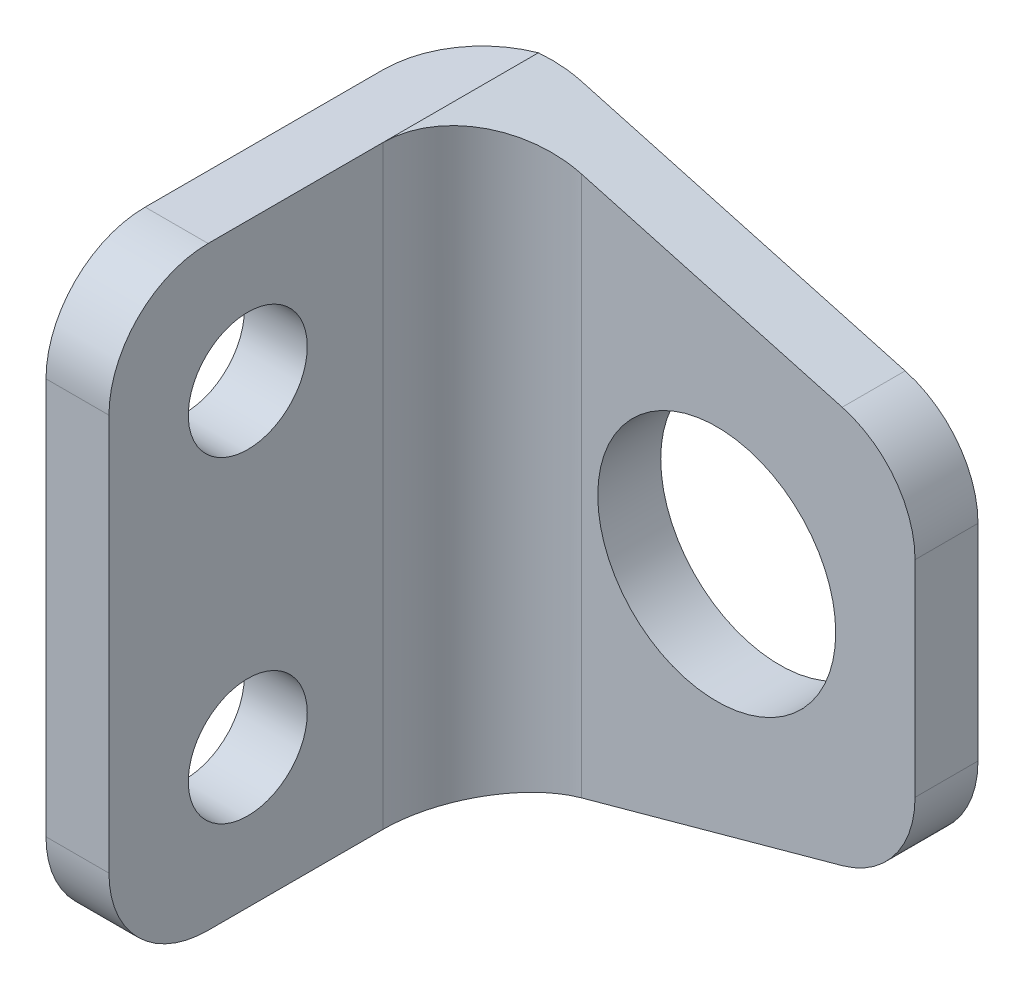
SolidWorks part; units mm, degrees
ref_plane "Front Plane" through (0, 0, 0) normal (0, 0, 1) x (1, 0, 0)
ref_plane "Top Plane" through (0, 0, 0) normal (0, 1, 0) x (1, 0, 0)
ref_plane "Right Plane" through (0, 0, 0) normal (1, 0, 0) x (0, 0, -1)
sketch "Sketch1" plane through (0, 0, 0) normal (1, 0, 0) x (0, 0, -1)
  line L1 (0, 0) -> (22, 0)
  line L2 (0, 0) -> (0, 30)
  line L3 (0, 30) -> (22, 30)
  line L4 (22, 0) -> (22, 30)
  dimension "D1" = 22
  dimension "D2" = 30
extrude "Boss-Extrude1" add sketch "Sketch1" along normal blind 3.175
sketch "Sketch2" plane through (0, 0, -22) normal (0, 0, -1) x (-1, 0, 0)
  line L5 (0, 0) -> (-25, 0)
  line L6 (0, 0) -> (0, 30)
  line L7 (0, 30) -> (-25, 30)
  line L8 (-25, 0) -> (-25, 30)
  dimension "D1" = 25
extrude "Boss-Extrude2" add sketch "Sketch2" against normal blind 3.175
sketch "Sketch3" plane through (0, 0, -22) normal (0, 0, -1) x (-1, 0, 0)
  line L0 (-25, 30) -> (-25, 0) construction
  circle A0 centre (-15, 15) radius 6
  point P4 (-25, 15)
  dimension "D2" = 12
  dimension "D1" = 10
extrude "Cut-Extrude1" cut sketch "Sketch3" against normal through all
sketch "Sketch5" plane through (0, 0, -22) normal (0, 0, -1) x (-1, 0, 0)
  line L4 (-3.175, 30) -> (-25, 24)
  line L9 (-25, 30) -> (-25, 0) construction
  line L10 (-25, 24) -> (-25, 30)
  line L11 (-25, 30) -> (-3.175, 30)
  line L12 (-25, 15) -> (0, 15) construction
  line L13 (-25, 30) -> (-25, 0) construction
  line L14 (0, 0) -> (0, 30) construction
  line L15 (-25, 0) -> (-3.175, 0)
  line L16 (-25, 6) -> (-25, 0)
  line L17 (-3.175, 0) -> (-25, 6)
  dimension "D1" = 6
extrude "Cut-Extrude4" cut sketch "Sketch5" against normal up to next
fillet "Fillet1" radius 5 6 edges at (1.5875, 30, 0) (1.5875, 0, 0) (0, 15, -22) (3.175, 15, -18.825) (25, 6, -20.4125) (25, 24, -20.4125)
sketch "Sketch4" plane through (3.175, 0, 0) normal (1, 0, 0) x (0, 0, -1)
  line L0 (0, 25) -> (0, 5) construction
  line L1 (13.825, 30) -> (5, 30) construction
  line L2 (5, 0) -> (13.825, 0) construction
  circle A0 centre (7, 23) radius 3
  circle A1 centre (7, 7) radius 3
  dimension "D2" = 7
  dimension "D3" = 6
  dimension "D1" = 7
  dimension "D4" = 7
extrude "Cut-Extrude2" cut sketch "Sketch4" against normal through all
